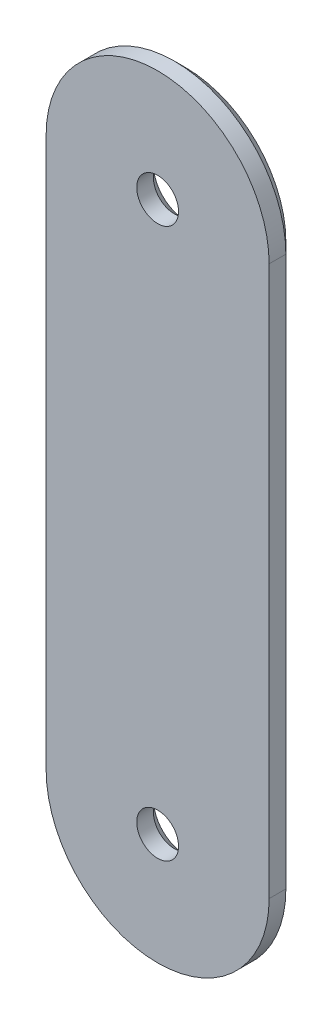
SolidWorks part; units mm, degrees
ref_plane "Front Plane" through (0, 0, 0) normal (1, 0, 0) x (0, 1, 0)
ref_plane "Top Plane" through (0, 0, 0) normal (0, 0, 1) x (0, 1, 0)
ref_plane "Right Plane" through (0, 0, 0) normal (0, 1, 0) x (-1, 0, 0)
sketch "Sketch1" plane through (0, 0, 0) normal (0, 0, 1) x (0, 1, 0)
  line L0 (0, 0) -> (-125.222, 0) construction
  line L1 (0, -25.4) -> (-125.222, -25.4)
  line L2 (0, 25.4) -> (-125.222, 25.4)
  arc A0 (0, -25.4) -> (0, 25.4) centre (0, 0) ccw
  arc A1 (-125.222, 25.4) -> (-125.222, -25.4) centre (-125.222, 0) ccw
  point P3 (-62.611, 0)
  dimension "D2" = 25.4
  dimension "D1" = 125.222
extrude "Boss-Extrude1" add sketch "Sketch1" along normal blind 6.35 contours A1 L1 A0 L2
sketch "Sketch2" plane through (0, 0, 6.35) normal (0, 0, 1) x (1, 0, 0)
  circle A0 centre (0, 0) radius 4.7625
  circle A1 centre (0, -125.222) radius 4.7625
  dimension "D1" = 9.525
extrude "Cut-Extrude1" cut sketch "Sketch2" against normal through all
chamfer "Chamfer1" distance 2.54 angle 45 6 edges at (0, -150.622, 0) (25.4, -62.611, 0) (0, 25.4, 0) (-25.4, -62.611, 0) (4.7625, -125.222, 0) (4.7625, 0, 0)
